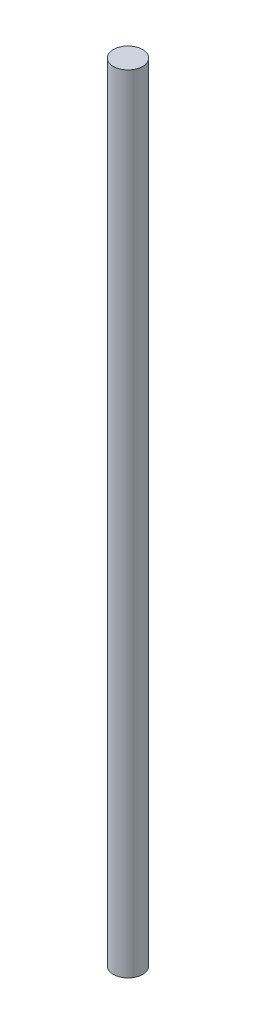
SolidWorks part; units mm, degrees
ref_plane "Front Plane" through (0, 0, 0) normal (0, 0, 1) x (1, 0, 0)
ref_plane "Top Plane" through (0, 0, 0) normal (0, 1, 0) x (1, 0, 0)
ref_plane "Right Plane" through (0, 0, 0) normal (1, 0, 0) x (0, 0, -1)
sketch "Sketch1" plane through (0, 0, 0) normal (0, 1, 0) x (1, 0, 0)
  circle A0 centre (0, 0) radius 1.4224
  dimension "D1" = 2.8448
extrude "Boss-Extrude1" add sketch "Sketch1" along normal blind 76.2
